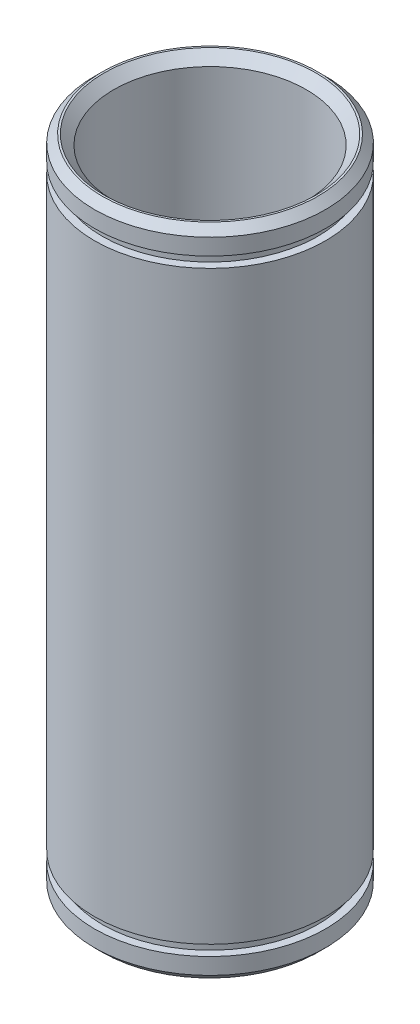
SolidWorks part; units mm, degrees
material "1023 Carbon Steel Sheet (SS)"
ref_plane "Front Plane" through (0, 0, 0) normal (0, 0, 1) x (1, 0, 0)
ref_plane "Top Plane" through (0, 0, 0) normal (0, 1, 0) x (1, 0, 0)
ref_plane "Right Plane" through (0, 0, 0) normal (1, 0, 0) x (0, 0, -1)
sketch "Sketch1" plane through (0, 0, 0) normal (0, 1, 0) x (1, 0, 0)
  circle A0 centre (0, 0) radius 15
  circle A1 centre (0, 0) radius 12.5
  dimension "D1" = 30
  dimension "D2" = 25
extrude "Boss-Extrude1" add sketch "Sketch1" along normal blind 85
ref_plane "Plane1" through (0, 81.875, 0) normal (0, 1, 0) x (1, 0, 0)
ref_plane "Plane2" through (0, 42.5, 0) normal (0, 1, 0) x (1, 0, 0)
sketch "Sketch2" plane through (0, 81.875, 0) normal (0, 1, 0) x (1, 0, 0)
  circle A0 centre (0, 0) radius 15 construction
  circle A1 centre (0, 0) radius 15
  circle A2 centre (0, 0) radius 14
  dimension "D1" = 28
extrude "Cut-Extrude1" cut sketch "Sketch2" against normal blind 1.375 contours A1 A2
mirror "Mirror1" about plane through (0, 42.5, 0) normal (0, 1, 0) of "Cut-Extrude1"
chamfer "Chamfer1" distance 1.25 angle 45 2 edges at (0, 85, 12.5) (0, 0, 12.5)
chamfer "Chamfer2" distance 1 angle 45 2 edges at (0, 85, 15) (0, 0, 15)
